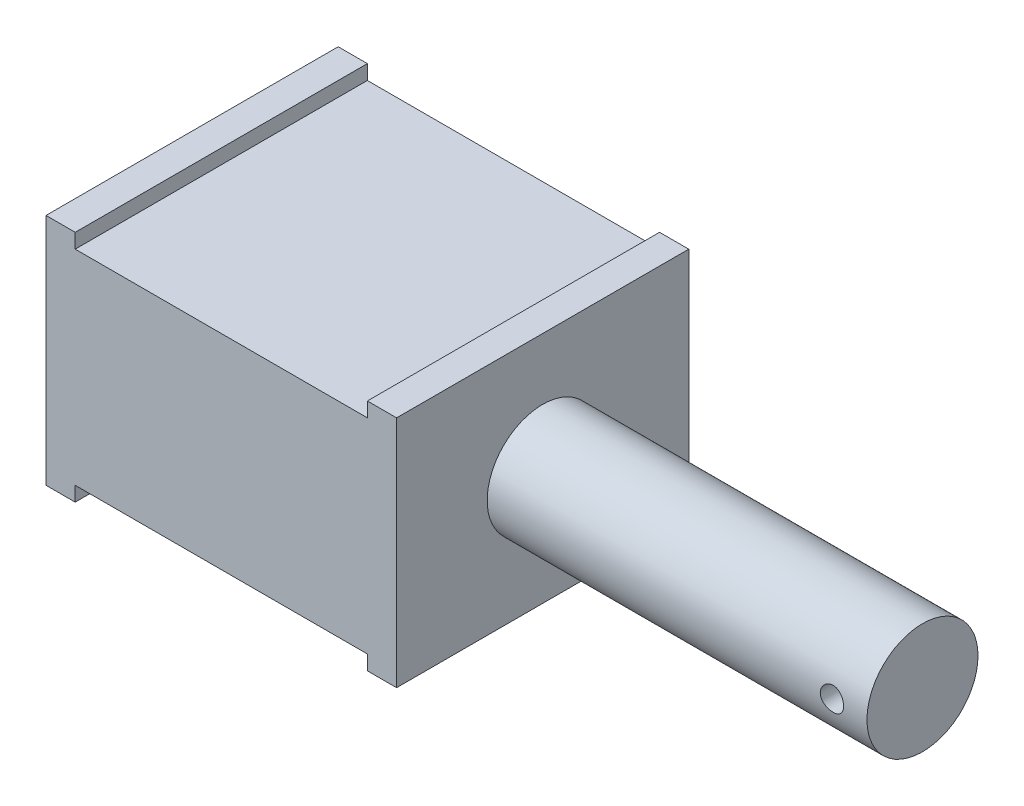
SolidWorks part; units mm, degrees
ref_plane "Front Plane" through (0, 0, 0) normal (0, 0, 1) x (1, 0, 0)
ref_plane "Top Plane" through (0, 0, 0) normal (0, 1, 0) x (1, 0, 0)
ref_plane "Right Plane" through (0, 0, 0) normal (1, 0, 0) x (0, 0, -1)
sketch "Sketch1" plane through (0, 0, 0) normal (1, 0, 0) x (0, 0, -1)
  line L1 (0, 0) -> (10, 0)
  line L2 (0, 0) -> (0, 8)
  line L3 (0, 8) -> (10, 8)
  line L4 (10, 0) -> (10, 8)
  dimension "D1" = 8
  dimension "D2" = 10
extrude "Boss-Extrude5" add sketch "Sketch1" along normal blind 12
sketch "Sketch2" plane through (12, 0, 0) normal (1, 0, 0) x (0, 0, -1)
  line L0 (10, 8) -> (0, 8) construction
  line L1 (10, 0) -> (10, 8) construction
  circle A0 centre (5, 4) radius 1.9
  dimension "D1" = 3.8
  dimension "D2" = 4
  dimension "D3" = 5
extrude "Boss-Extrude6" add sketch "Sketch2" along normal blind 13
ref_plane "Plane1" through (0, 0, -5) normal (0, 0, -1) x (-1, 0, 0)
sketch "Sketch3" plane through (0, 0, -5) normal (0, 0, -1) x (-1, 0, 0)
  line L0 (-25, 4) -> (-23.8, 4) construction
  line L1 (-25, 5.9) -> (-25, 2.1) construction
  circle A0 centre (-23.8, 4) radius 0.4
  dimension "D2" = 0.8
  dimension "D1" = 1.2
extrude "Cut-Extrude1" cut sketch "Sketch3" against normal blind 3 and the other way blind 3
sketch "Sketch4" plane through (0, 0, -10) normal (0, 0, -1) x (-1, 0, 0)
  line L0 (-12, 8) -> (-11, 8) construction
  line L1 (-12, 8) -> (0, 8) construction
  line L2 (-11, 8) -> (-1, 8)
  line L4 (-11, 8) -> (-11, 7.5)
  line L5 (-11, 7.5) -> (-1, 7.5)
  line L6 (-1, 7.5) -> (-1, 8)
  line L7 (-12, 0) -> (0, 0) construction
  line L8 (-11, 0.5) -> (-1, 0.5)
  line L9 (-11, 0.5) -> (-11, 0)
  line L10 (-11, 0) -> (-1, 0)
  line L11 (-1, 0.5) -> (-1, 0)
  line L12 (0, 4.4) -> (0, -4.4) construction
  line L13 (-12, 0) -> (-12, 8) construction
  dimension "D1" = 1
  dimension "D2" = 1
  dimension "D3" = 7
  dimension "D4" = 1
  dimension "D5" = 1
  dimension "D6" = 0.5
extrude "Cut-Extrude2" cut sketch "Sketch4" against normal blind 10
scale "Scale1" scale about origin uniform scaling yes scale factor 1.5
